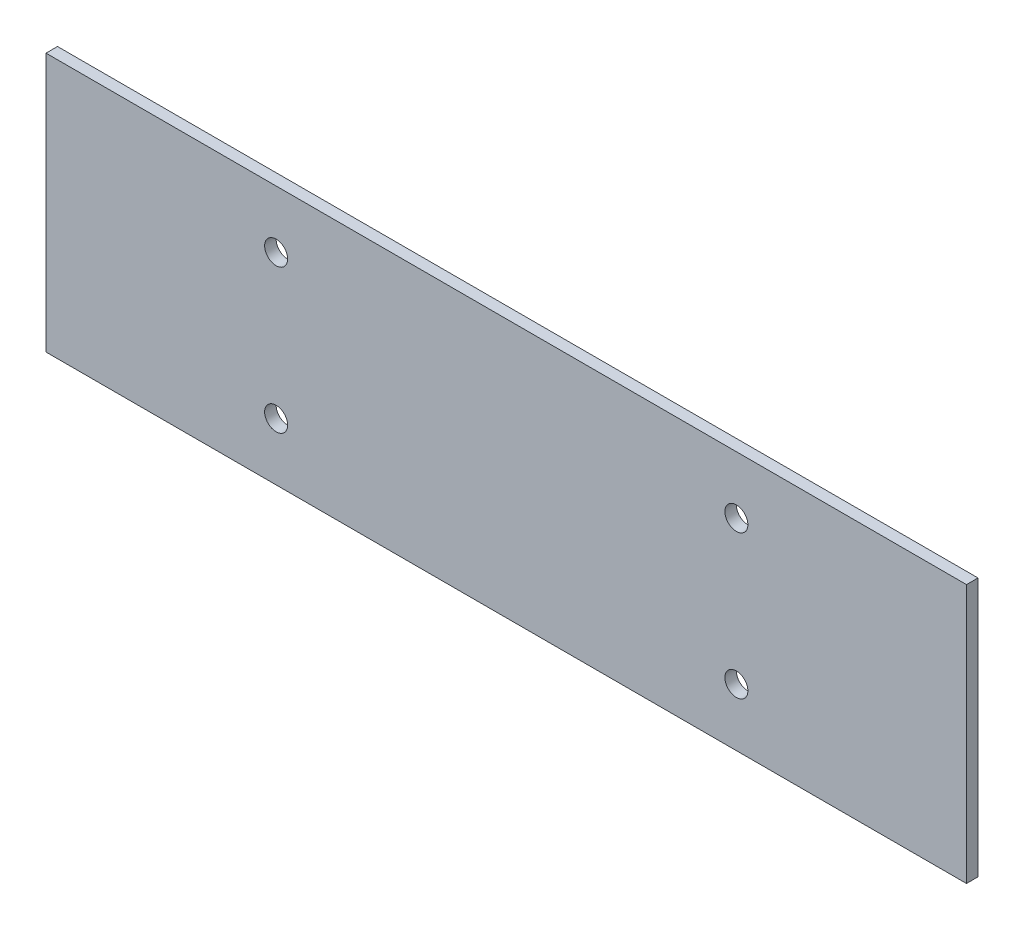
SolidWorks part; units mm, degrees
ref_plane "Ön Düzlem" through (0, 0, 0) normal (0, 0, 1) x (1, 0, 0)
ref_plane "Üst Düzlem" through (0, 0, 0) normal (0, 1, 0) x (1, 0, 0)
ref_plane "Sağ Düzlem" through (0, 0, 0) normal (1, 0, 0) x (0, 0, -1)
sketch "Çizim1" plane through (0, 0, 0) normal (0, 0, 1) x (1, 0, 0)
  line L1 (0, 0) -> (160, 0)
  line L2 (0, 0) -> (0, 45)
  line L3 (0, 45) -> (160, 45)
  line L4 (160, 0) -> (160, 45)
  line L5 (40, 35) -> (120, 35) construction
  line L6 (40, 35) -> (40, 10) construction
  line L7 (40, 10) -> (120, 10) construction
  line L8 (120, 35) -> (120, 10) construction
  circle A0 centre (40, 35) radius 2
  circle A1 centre (120, 35) radius 2
  circle A2 centre (40, 10) radius 2
  circle A3 centre (120, 10) radius 2
  dimension "D1" = 160
  dimension "D2" = 45
  dimension "D3" = 40
  dimension "D4" = 10
  dimension "D5" = 25
  dimension "D6" = 80
extrude "Yükseklik-Ekstrüzyon1" add sketch "Çizim1" along normal blind 2
